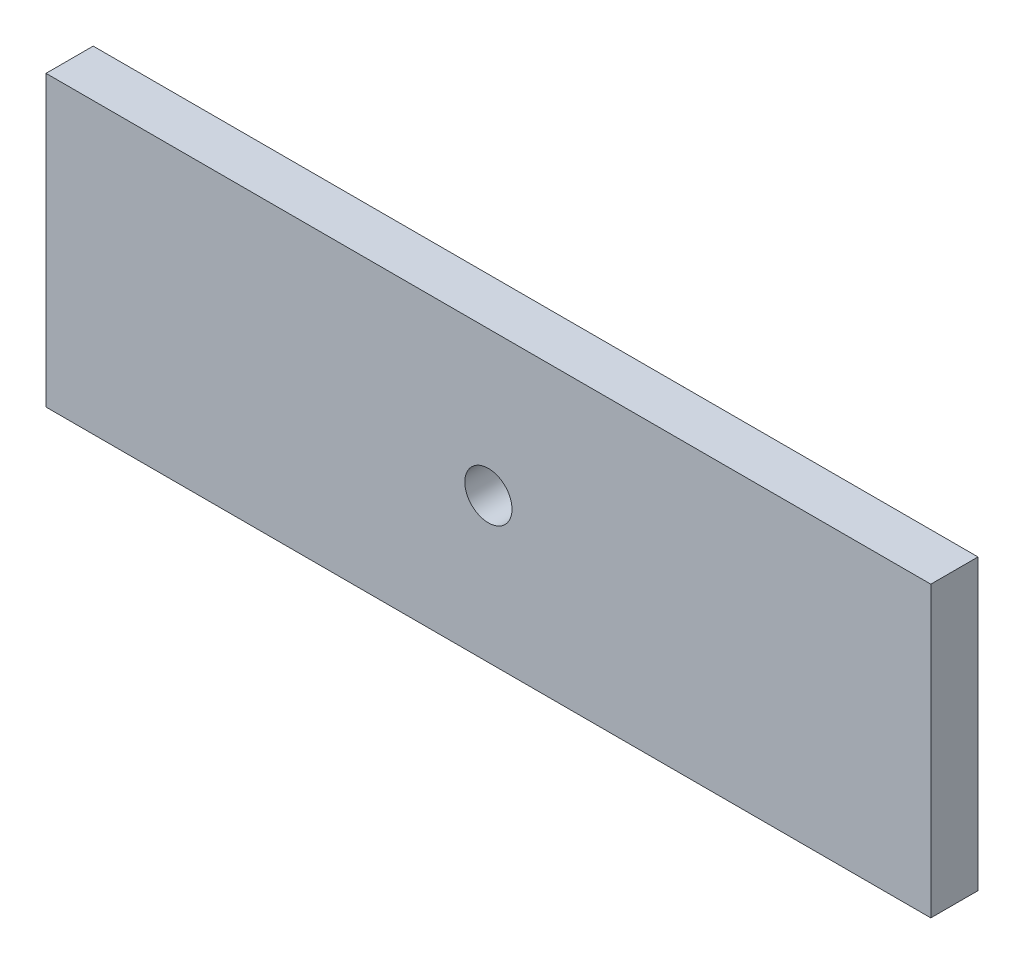
SolidWorks part; units mm, degrees
ref_plane "Alzado" through (0, 0, 0) normal (0, 0, 1) x (1, 0, 0)
ref_plane "Planta" through (0, 0, 0) normal (0, 1, 0) x (1, 0, 0)
ref_plane "Vista lateral" through (0, 0, 0) normal (1, 0, 0) x (0, 0, -1)
sketch "Croquis1" plane through (0, 0, 0) normal (0, 0, 1) x (1, 0, 0)
  line L0 (0, 0) -> (4, 0) construction
  line L1 (37.5, 12.25) -> (-37.5, 12.25)
  line L2 (37.5, 12.25) -> (37.5, -12.25)
  line L3 (37.5, -12.25) -> (-37.5, -12.25)
  line L4 (-37.5, 12.25) -> (-37.5, -12.25)
  line L5 (37.5, 12.25) -> (-37.5, -12.25) construction
  line L6 (37.5, -12.25) -> (-37.5, 12.25) construction
  line L7 (0, 12.25) -> (0, -12.25) construction
  line L8 (4, 12.25) -> (4, -12.25) construction
  line L9 (-37.5, 4) -> (37.5, 4) construction
  line L10 (0, 0) -> (4, 4) construction
  line L11 (-37.5, 0) -> (37.5, 0) construction
  line L12 (7, 12.25) -> (7, -12.25) construction
  line L13 (-37.5, -4) -> (37.5, -4) construction
  circle A0 centre (0, 0) radius 2
  point P0 (0, 0)
  dimension "D1" = 7
  dimension "D2" = 8
extrude "Saliente-Extruir1" add sketch "Croquis1" along normal blind 4
